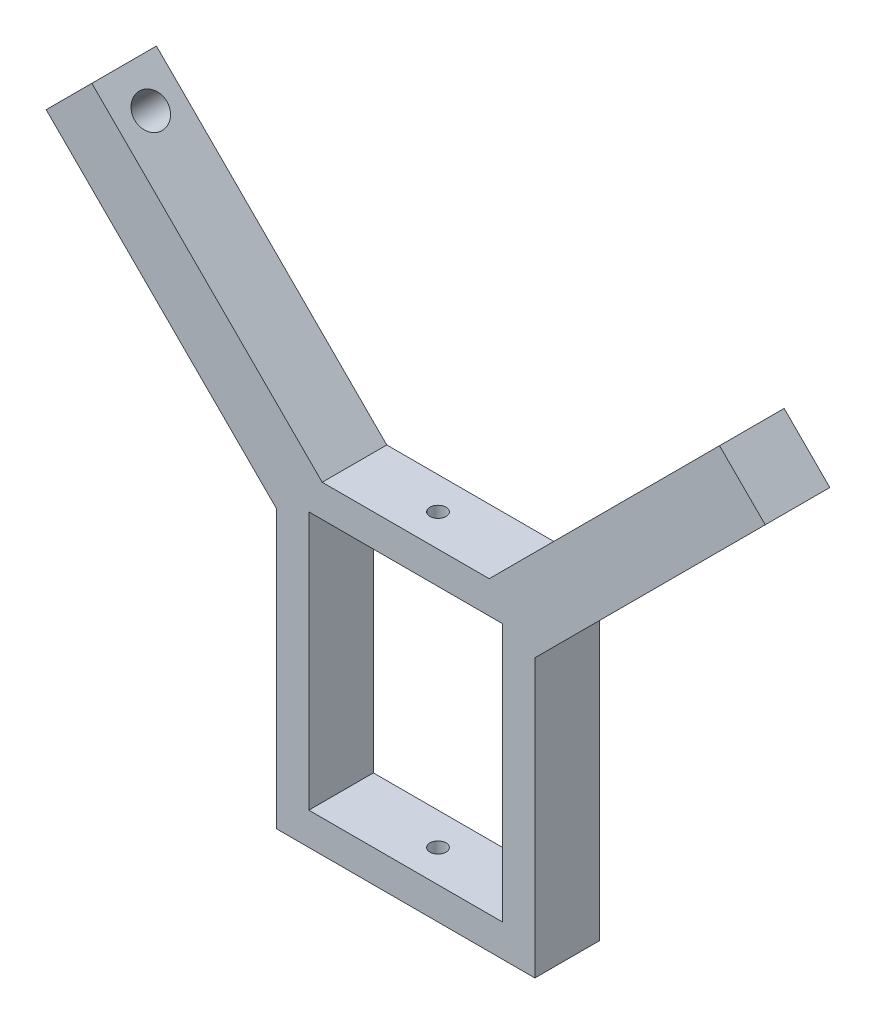
SolidWorks part; units mm, degrees
ref_plane "Front Plane" through (0, 0, 0) normal (0, 0, 1) x (1, 0, 0)
ref_plane "Top Plane" through (0, 0, 0) normal (0, 1, 0) x (1, 0, 0)
ref_plane "Right Plane" through (0, 0, 0) normal (1, 0, 0) x (0, 0, -1)
sketch "Sketch1" plane through (0, 0, 0) normal (0, 0, 1) x (1, 0, 0)
  line L1 (20, -100) -> (80, -100)
  line L2 (20, -100) -> (20, -180)
  line L3 (20, -180) -> (80, -180)
  line L4 (80, -100) -> (80, -180)
  dimension "D2" = 60
  dimension "D4" = 80
extrude "Extrude-Thin1" add sketch "Sketch1" along normal mid plane 20 thin thin type one direction wall 10
sketch "Sketch2" plane through (0, 0, 0) normal (0, 0, 1) x (1, 0, 0)
  line L0 (20, -100) -> (-54.2462, -25.7538) construction
  line L1 (90, -90) -> (10, -90) construction
  line L2 (27.0711, -92.9289) -> (-47.1751, -18.6827)
  line L3 (12.9289, -107.0711) -> (-61.3173, -32.8249)
  line L4 (27.0711, -92.9289) -> (12.9289, -107.0711)
  line L5 (-47.1751, -18.6827) -> (-61.3173, -32.8249)
  dimension "D1" = 135
  dimension "D2" = 105
  dimension "D3" = 10
  dimension "D4" = 10
extrude "Boss-Extrude1" add sketch "Sketch2" along normal mid plane 20
sketch "Sketch3" plane through (-47.0711, -47.0711, 0) normal (-0.7071, -0.7071, 0) x (0, 0, 1)
  circle A0 centre (0, 8.4853) radius 5
extrude "Cut-Extrude1" cut sketch "Sketch3" against normal up to next
ref_plane "Plane1" through (50, 0, 0) normal (1, 0, 0) x (0, 0, -1)
mirror "Mirror1" about plane through (50, 0, 0) normal (1, 0, 0) of "Cut-Extrude1", "Boss-Extrude1"
sketch "Sketch4" plane through (0, -90, 0) normal (0, 1, 0) x (1, 0, 0)
  circle A0 centre (50, 0) radius 2.5
  dimension "D1" = 5
extrude "Cut-Extrude2" cut sketch "Sketch4" against normal through all and the other way through all
